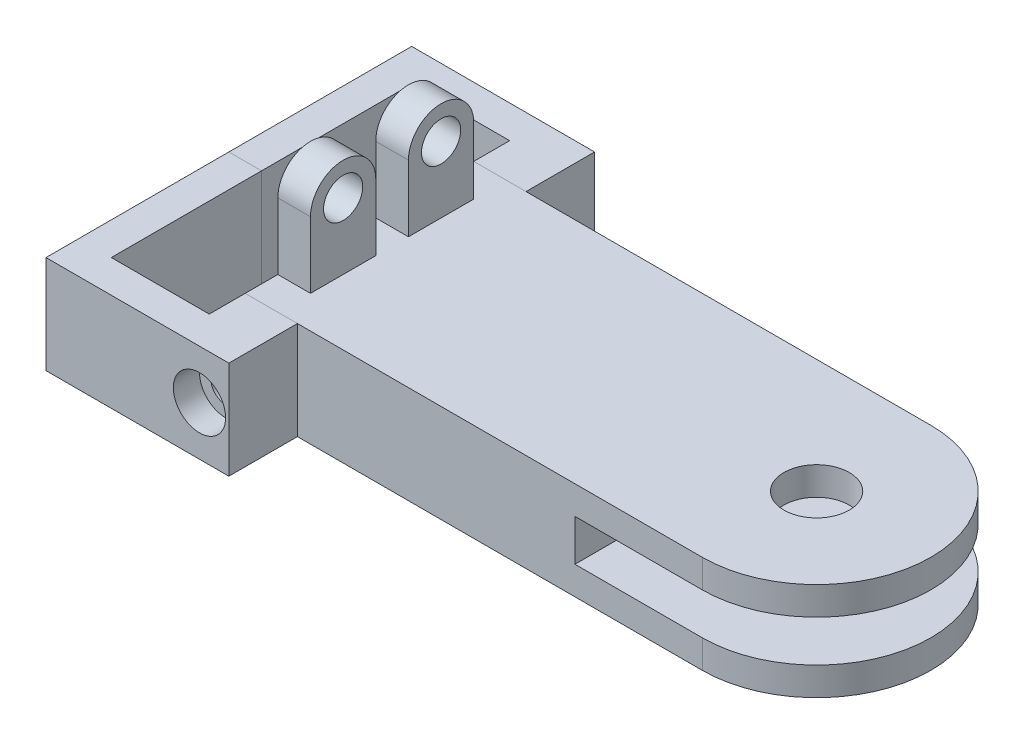
SolidWorks part; units mm, degrees
ref_plane "Front Plane" through (0, 0, 0) normal (0, 0, 1) x (1, 0, 0)
ref_plane "Top Plane" through (0, 0, 0) normal (0, 1, 0) x (1, 0, 0)
ref_plane "Right Plane" through (0, 0, 0) normal (1, 0, 0) x (0, 0, -1)
sketch "Sketch1" plane through (0, 0, 0) normal (0, 1, 0) x (1, 0, 0)
  line L0 (0, 17.5) -> (-70, 17.5)
  line L1 (-70, 17.5) -> (-70, -17.5)
  line L2 (-70, -17.5) -> (0, -17.5)
  arc A0 (0, -17.5) -> (0, 17.5) centre (0, 0) ccw
  circle A1 centre (0, 0) radius 5
  dimension "D1" = 35
  dimension "D2" = 10
  dimension "D3" = 70
extrude "Boss-Extrude2" add sketch "Sketch1" along normal mid plane 15
sketch "Sketch4" plane through (0, 0, 0) normal (0, 0, 1) x (1, 0, 0)
  line L1 (-19.5, 3.175) -> (17.5, 3.175)
  line L2 (-19.5, 3.175) -> (-19.5, -3.175)
  line L3 (-19.5, -3.175) -> (17.5, -3.175)
  line L4 (17.5, 3.175) -> (17.5, -3.175)
  line L5 (17.5, -7.5) -> (17.5, 7.5) construction
  line L6 (19.25, 0) -> (-19.25, 0) construction
  point P10 (-19.5, 0)
  dimension "D1" = 6.35
  dimension "D2" = 37
extrude "Cut-Extrude2" cut sketch "Sketch4" against normal through all and the other way through all
ref_plane "Plane1" through (-50, 0, 0) normal (-1, 0, 0) x (0, 0, 1)
sketch "Sketch5" plane through (-50, 0, 0) normal (-1, 0, 0) x (0, 0, 1)
  line L0 (-17.5, 7.5) -> (17.5, 7.5) construction
  line L1 (-17.5, -7.5) -> (-26.5, -7.5)
  line L2 (-17.5, -7.5) -> (-17.5, 7.5)
  line L3 (-20, 27.5) -> (-26.5, 27.5)
  line L4 (-26.5, -7.5) -> (-26.5, 27.5)
  line L6 (-17.5, 7.5) -> (-20, 7.5)
  line L9 (-20, 7.5) -> (-20, 27.5)
  line L11 (17.5, 7.5) -> (-17.5, 7.5) construction
  dimension "D1" = 20
  dimension "D2" = 2.5
  dimension "D3" = 9
extrude "Boss-Extrude4" [suppressed] add sketch "Sketch5" along normal blind 3
mirror "Mirror1" [suppressed] about plane through (0, 0, 0) normal (0, 0, 1)
sketch "Sketch6" plane through (-70, 0, 0) normal (-1, 0, 0) x (0, 0, 1)
  line L0 (-17.5, 7.5) -> (17.5, 7.5) construction
  line L1 (-12.5, 7.5) -> (-2.5, 7.5)
  line L2 (-12.5, 7.5) -> (-12.5, 17.66)
  line L4 (-2.5, 7.5) -> (-2.5, 17.66)
  line L6 (12.5, 7.5) -> (2.5, 7.5)
  line L7 (12.5, 7.5) -> (12.5, 17.66)
  line L9 (2.5, 7.5) -> (2.5, 17.66)
  line L10 (0, -19.25) -> (0, 19.25) construction
  arc A0 (2.5, 17.66) -> (12.5, 17.66) centre (7.5, 17.66) cw
  arc A1 (-12.5, 17.66) -> (-2.5, 17.66) centre (-7.5, 17.66) cw
  circle A2 centre (-7.5, 17.66) radius 3
  circle A3 centre (7.5, 17.66) radius 3
  dimension "D7" = 6
  dimension "D8" = 6
  dimension "D1" = 10.16
  dimension "D2" = 10
  dimension "D5" = 15
  dimension "D6" = 2.5
extrude "Boss-Extrude5" add sketch "Sketch6" against normal blind 5
sketch "Sketch8" plane through (0, 0, 0) normal (0, 1, 0) x (1, 0, 0)
  line L0 (0, 17.5) -> (-70, 17.5) construction
  line L1 (-62, 17.5) -> (-70, 17.5)
  line L2 (-62, 17.5) -> (-62, 28)
  line L3 (-62, 28) -> (-90, 28)
  line L4 (-90, 17.5) -> (-90, 28)
  line L5 (-70, 17.5) -> (-70, 12.5) construction
  line L7 (-90, 17.5) -> (-90, 0)
  line L8 (-90, 0) -> (-85, 0)
  line L9 (-85, 17.5) -> (-85, 0)
  line L11 (-85, 17.5) -> (-85, 23)
  line L12 (-85, 23) -> (-70, 23)
  line L13 (-70, 17.5) -> (-70, 23)
  dimension "D1" = 10.5
  dimension "D2" = 5.5
  dimension "D3" = 8
  dimension "D4" = 5
  dimension "D5" = 15
extrude "Boss-Extrude6" add sketch "Sketch8" along normal up to surface and the other way up to surface separate body up to face at (-55.2083, 7.5, 0) other way up to face at (-30.625, -7.5, 0)
sketch "Sketch9" plane through (0, 0, -23) normal (0, 0, 1) x (1, 0, 0)
  line L0 (19.25, 0) -> (-19.25, 0) construction
  line L1 (-85, 7.5) -> (-70, 7.5) construction
  circle A0 centre (-77.5, 0) radius 2.5
  point P6 (-77.5, 7.5)
  dimension "D1" = 5
extrude "Boss-Extrude7" add sketch "Sketch9" along normal blind 3
mirror "Mirror3" about plane through (0, 0, 0) normal (0, 0, 1) of bodies 110
hole_wizard "CBORE for M4 SHCS1" positions "Sketch12" profile "Sketch13" counterbore size "M4" standard "ANSI Metric"
sketch "Sketch12" plane through (0, 0, 28) normal (0, 0, 1) x (1, 0, 0)
  line L1 (-70, 7.5) -> (-70, -7.5) construction
  line L2 (-90, -7.5) -> (-62, -7.5) construction
  point P0 (-66.5, 0)
  dimension "D1" = 3.5
  dimension "D2" = 7.5
sketch "Sketch13" plane through (-66.5, 0, 28) normal (1, 0, 0) x (0, -1, 0)
  line L0 (0, 0) -> (0, 11.8519)
  line L1 (0, 11.8519) -> (2.25, 10.5)
  line L2 (2.25, 10.5) -> (2.25, 4)
  line L3 (2.25, 4) -> (4, 4)
  line L4 (4, 4) -> (4, 0)
  line L5 (4, 0) -> (0, 0)
  line L10 (0, 11.8519) -> (-2.25, 10.5) construction
  line L11 (0, -6.35) -> (0, 107.95) construction
  dimension "Hole Dia." = 4.5
  dimension "Hole Depth" = 10.5
  dimension "C'Bore Dia." = 8
  dimension "C'Bore Depth" = 4
  dimension "Drill Angle" = 118
mirror "Mirror5" about plane through (0, 0, 0) normal (0, 0, 1) of "CBORE for M4 SHCS1"
hole_wizard "Ø4.0mm Dowel Hole1" positions "Sketch14" profile "Sketch15" hole size "Ø4.0" standard "ANSI Metric" end condition through all
sketch "Sketch14" plane through (0, 0, 17.5) normal (0, 0, 1) x (1, 0, 0)
  point P0 (-66.5, 0)
sketch "Sketch15" plane through (-66.5, 0, 17.5) normal (1, 0, 0) x (0, -1, 0)
  line L0 (0, 0) -> (0, 45.5)
  line L1 (0, 45.5) -> (2, 45.5)
  line L2 (2, 45.5) -> (2, 0)
  line L5 (2, 0) -> (0, 0)
  line L11 (0, -6.35) -> (0, 107.95) construction
  dimension "Thru Hole Dia." = 4
  dimension "Thru Hole Depth" = 45.5
delete or keep bodies "Corps-Supprimer/Garder 1" [suppressed] type delete bodies bodies 113
delete or keep bodies "Corps-Supprimer/Garder 2" [suppressed] type delete bodies bodies 116
